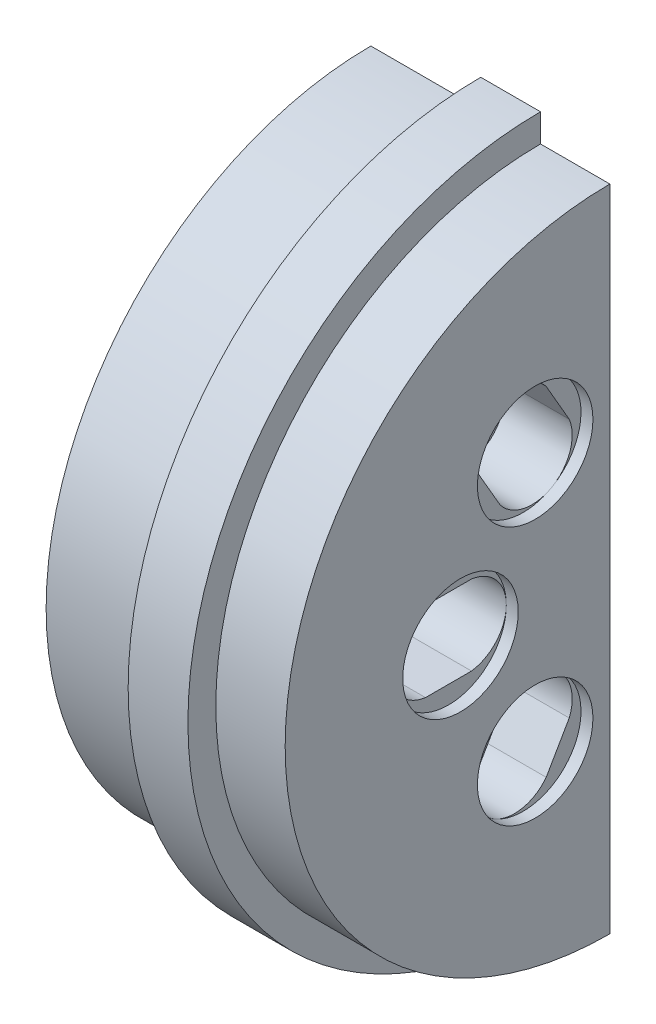
SolidWorks part; units mm, degrees
material "PE1000 Высокой плотности"
ref_plane "Спереди" through (0, 0, 0) normal (0, 0, 1) x (1, 0, 0)
ref_plane "Сверху" through (0, 0, 0) normal (0, 1, 0) x (1, 0, 0)
ref_plane "Справа" through (0, 0, 0) normal (1, 0, 0) x (0, 0, -1)
sketch "Эскиз1" plane through (0, 0, 0) normal (0, 0, 1) x (1, 0, 0)
  line L0 (12.5885, -88.5) -> (-2.4115, -88.5)
  line L1 (-2.4115, -88.5) -> (-2.4115, -81.5)
  line L2 (-2.4115, -81.5) -> (-30, -81.5)
  line L3 (-30, -81.5) -> (-30, 0)
  line L4 (-30, 0) -> (30, 0)
  line L5 (0, 0) -> (-524.9579, 0) construction
  line L6 (0, -55) -> (0, 55) construction
  line L7 (12.5885, -88.5) -> (12.5885, -81.5)
  line L9 (30, -81.5) -> (30, 0)
  line L10 (12.5885, -81.5) -> (30, -81.5)
  line L11 (5.0885, -88.5) -> (5.0885, -48.758) construction
  dimension "D1" = 177
  dimension "D2" = 163
  dimension "D3" = 60
  dimension "D4" = 15
  dimension "D5" = 35.0885
  dimension "D6" = 27.5885
revolve "Повернуть1" add sketch "Эскиз1" angle 180 about L5
sketch "Эскиз2" plane through (30, 0, 0) normal (1, 0, 0) x (0, 0, -1)
  circle A0 centre (0, 0) radius 37.5 construction
  circle A1 centre (-37.5, 0) radius 6.6
  circle A2 centre (-18.75, 32.476) radius 6.6
  circle A3 centre (18.75, 32.476) radius 6.6
  circle A4 centre (37.5, 0) radius 6.6
  circle A5 centre (18.75, -32.476) radius 6.6
  circle A6 centre (-18.75, -32.476) radius 6.6
  point P17 (0, 0)
  dimension "D1" = 75
  dimension "D2" = 13.2
  dimension "D3" = 6
extrude "Вырез-Вытянуть1" cut sketch "Эскиз2" against normal through all
sketch "Эскиз5" plane through (30, 0, 0) normal (1, 0, 0) x (0, 0, -1)
  line L0 (-18.75, 32.476) -> (-12.9765, 22.476) construction
  line L7 (-24.5235, 22.476) -> (-12.9765, 22.476) construction
  line L8 (-12.9765, 22.476) -> (-7.203, 32.476) construction
  line L9 (-7.203, 32.476) -> (-12.9765, 42.476)
  line L10 (-12.9765, 42.476) -> (-24.5235, 42.476) construction
  line L11 (-24.5235, 42.476) -> (-30.297, 32.476) construction
  line L12 (-30.297, 32.476) -> (-24.5235, 22.476)
  line L19 (-12.9765, 22.476) -> (0, 0) construction
  line L20 (-37.5, 0) -> (0, 0) construction
  line L21 (24.5235, 22.476) -> (30.297, 32.476)
  line L22 (12.9765, 42.476) -> (7.203, 32.476)
  line L23 (31.7265, -10) -> (43.2735, -10)
  line L24 (43.2735, 10) -> (31.7265, 10)
  line L25 (7.203, -32.476) -> (12.9765, -42.476)
  line L26 (30.297, -32.476) -> (24.5235, -22.476)
  line L27 (-24.5235, -22.476) -> (-30.297, -32.476)
  line L28 (-12.9765, -42.476) -> (-7.203, -32.476)
  line L29 (-31.7265, 10) -> (-43.2735, 10)
  line L30 (-43.2735, -10) -> (-31.7265, -10)
  arc A0 (24.5235, 22.476) -> (7.203, 32.476) centre (16.5465, 28.6593) cw
  circle A1 centre (-18.75, 32.476) radius 10 construction
  arc A2 (12.9765, 42.476) -> (30.297, 32.476) centre (20.9535, 36.2926) cw
  arc A3 (-7.203, 32.476) -> (-24.5235, 22.476) centre (-16.5465, 28.6593) cw
  arc A4 (-30.297, 32.476) -> (-12.9765, 42.476) centre (-20.9535, 36.2926) cw
  arc A5 (31.7265, -10) -> (31.7265, 10) centre (33.0929, 0) cw
  arc A6 (43.2735, 10) -> (43.2735, -10) centre (41.9071, 0) cw
  arc A7 (7.203, -32.476) -> (24.5235, -22.476) centre (16.5465, -28.6593) cw
  circle A8 centre (-18.75, 32.476) radius 14.5 construction
  arc A9 (30.297, -32.476) -> (12.9765, -42.476) centre (20.9535, -36.2926) cw
  arc A10 (-24.5235, -22.476) -> (-7.203, -32.476) centre (-16.5465, -28.6593) cw
  arc A11 (-12.9765, -42.476) -> (-30.297, -32.476) centre (-20.9535, -36.2926) cw
  arc A12 (-31.7265, 10) -> (-31.7265, -10) centre (-33.0929, 0) cw
  arc A13 (-43.2735, -10) -> (-43.2735, 10) centre (-41.9071, 0) cw
  point P48 (0, 0)
  dimension "D1" = 20
  dimension "D2" = 29
  dimension "D3" = 6
extrude "Вырез-Вытянуть2" cut sketch "Эскиз5" against normal blind 20
sketch "Эскиз6" plane through (30, 0, 0) normal (1, 0, 0) x (0, 0, -1)
  circle A0 centre (-37.5, 0) radius 14.5
  circle A1 centre (-18.75, -32.476) radius 14.5
  circle A2 centre (-18.75, 32.476) radius 14.5
  dimension "D1" = 29
extrude "Вырез-Вытянуть3" cut sketch "Эскиз6" against normal blind 3
sketch "Эскиз7" plane through (12.5885, 0, 0) normal (1, 0, 0) x (0, 0, -1)
  line L0 (-38.6996, 89.4635) -> (-32.3572, 74.8015)
  circle A0 centre (-38.6996, 89.4635) radius 8.975
  arc A1 (0, 88.5) -> (0, -88.5) centre (0, 0) ccw construction
  arc A2 (0, 81.5) -> (0, -81.5) centre (0, 0) ccw construction
  dimension "D1" = 17.95
move or copy body "Тело-Переместить/Копировать1" [suppressed] bodies to move or copy 103
